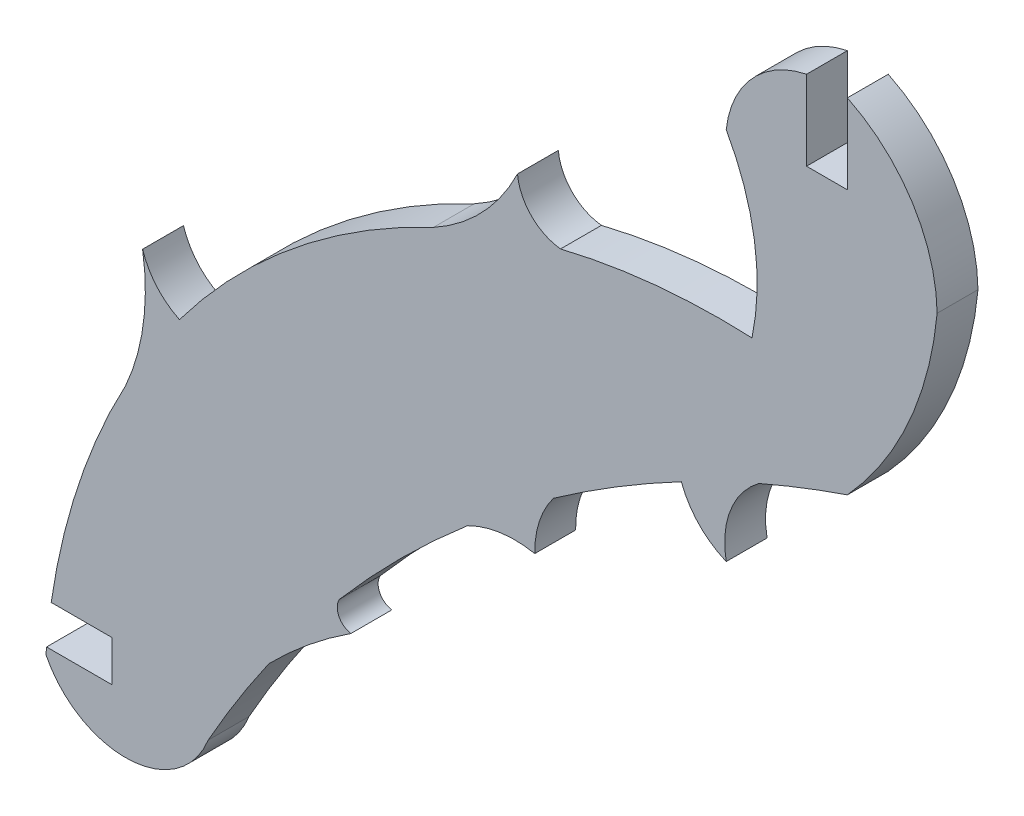
SolidWorks part; units mm, degrees
ref_plane "Front Plane" through (0, 0, 0) normal (0, 0, 1) x (1, 0, 0)
ref_plane "Top Plane" through (0, 0, 0) normal (0, 1, 0) x (1, 0, 0)
ref_plane "Right Plane" through (0, 0, 0) normal (1, 0, 0) x (0, 0, -1)
sketch "Sketch1" plane through (0, 0, 0) normal (0, 0, 1) x (1, 0, 0)
  line L0 (0, -11.3041) -> (1.524, -11.3041)
  line L1 (1.524, -11.3041) -> (1.524, -8.3331)
  line L2 (0, -11.3041) -> (0, -8.3331)
  line L4 (-25.8999, -39.4808) -> (-28.172, -39.4808)
  line L5 (-25.8999, -41.0048) -> (-28.3453, -41.0048)
  line L6 (-25.8999, -39.4808) -> (-25.8999, -41.0048)
  arc A0 (1.524, -8.3331) -> (4.8715, -13.6173) centre (-1.0965, -13.6955) cw
  arc A1 (4.8715, -13.6173) -> (1.524, -21.1578) centre (-8.0377, -12.3998) cw
  arc A2 (1.524, -21.1578) -> (-1.7754, -22.4393) centre (15.6219, -62.3422) ccw
  arc A3 (-22.3205, -41.0048) -> (-28.366, -41.2709) centre (-25.4021, -39.8011) cw
  arc A4 (0, -8.3331) -> (-2.9956, -11.622) centre (0.7552, -12.0296) ccw
  arc A5 (-2.9956, -11.622) -> (-2.0341, -17.8674) centre (-10.7814, -16.0174) cw
  arc A6 (-2.0341, -17.8674) -> (-9.1748, -18.5639) centre (-3.1778, -43.0957) ccw
  arc A7 (-28.3453, -41.0048) -> (-28.366, -41.2709) centre (-3.1778, -43.0957) ccw
  arc A8 (-1.7754, -22.4393) -> (-2.9956, -25.5725) centre (0.109, -24.9774) ccw
  arc A9 (-2.9956, -25.5725) -> (-4.6693, -23.8302) centre (-1.8403, -22.7876) cw
  arc A10 (-9.4372, -26.748) -> (-10.1358, -28.885) centre (-6.7072, -28.8231) ccw
  arc A11 (-10.1358, -28.885) -> (-12.6456, -29.2385) centre (-10.8806, -32.6839) ccw
  arc A12 (-20.0554, -37.4015) -> (-16.9925, -34.8939) centre (-7.1673, -50.0191) cw
  arc A13 (-16.9925, -34.8939) -> (-17.4283, -34.0122) centre (-16.9034, -34.3013) cw
  arc A14 (-20.0554, -37.4015) -> (-22.3205, -41.0048) centre (15.6219, -62.3422) ccw
  arc A15 (-12.6456, -29.2385) -> (-17.4283, -34.0122) centre (15.6219, -62.3422) ccw
  arc A16 (-4.6693, -23.8302) -> (-9.4372, -26.748) centre (15.6219, -62.3422) ccw
  arc A17 (-13.9196, -20.2399) -> (-10.7814, -16.9448) centre (-17.48, -13.7069) ccw
  arc A18 (-10.7814, -16.9448) -> (-9.1748, -18.5639) centre (-8.98, -16.7639) ccw
  arc A19 (-25.4021, -31.1016) -> (-24.7632, -26.3659) centre (-33.0045, -27.665) ccw
  arc A20 (-24.7632, -26.3659) -> (-23.3893, -27.954) centre (-22.2469, -25.5774) ccw
  arc A21 (-25.4021, -31.1016) -> (-28.172, -39.4808) centre (-3.1778, -43.0957) ccw
  arc A22 (-13.9196, -20.2399) -> (-23.3893, -27.954) centre (-3.1778, -43.0957) ccw
  point P23 (-29.4789, -39.4808)
  point P25 (-29.4789, -41.0048)
extrude "Boss-Extrude1" add sketch "Sketch1" along normal blind 1.524
